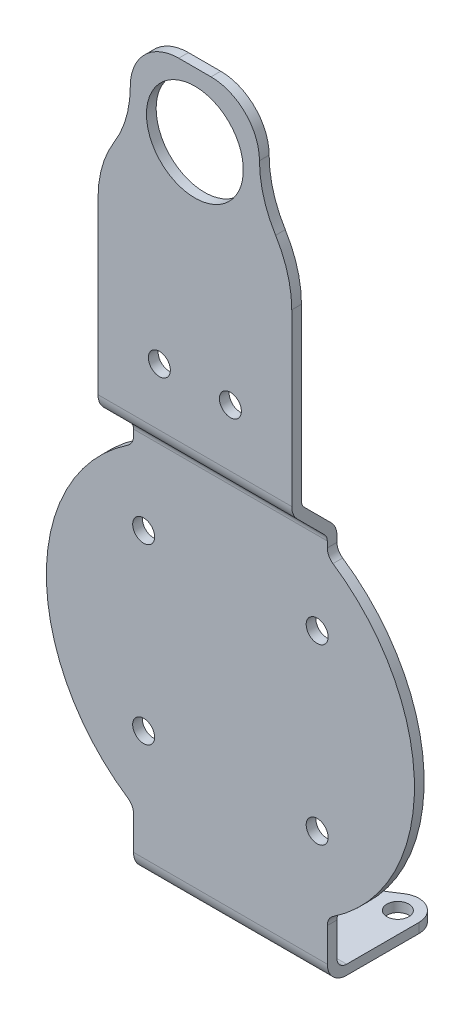
SolidWorks part; units mm, degrees
ref_plane "前视基准面" through (0, 0, 0) normal (0, 0, 1) x (1, 0, 0)
ref_plane "上视基准面" through (0, 0, 0) normal (0, 1, 0) x (1, 0, 0)
ref_plane "右视基准面" through (0, 0, 0) normal (1, 0, 0) x (0, 0, -1)
ref_plane "基准面1" through (15, 0, 0) normal (1, 0, 0) x (0, 0, -1)
sketch "草图1" plane through (15, 0, 0) normal (1, 0, 0) x (0, 0, -1)
  line L0 (-7, 32.3787) -> (-1.5, 26.8787)
  line L1 (-1.5, 26.8787) -> (-1.5, 32.3787)
  line L2 (-1.5, 32.3787) -> (-7, 32.3787)
extrude "凸台-拉伸1" add sketch "草图1" against normal blind 30
sketch "草图2" plane through (0, 0, 1.5) normal (0, 0, -1) x (-1, 0, 0)
  line L0 (-15, 24.2332) -> (-15, 32.3787)
  line L1 (-15, 32.3787) -> (15, 32.3787)
  line L2 (15, 32.3787) -> (15, 24.2332)
  line L3 (15, -24.2332) -> (-15, -24.2332)
  arc A0 (-15, -24.2332) -> (-15, 24.2332) centre (0, 0) cw
  arc A1 (15, 24.2332) -> (15, -24.2332) centre (0, 0) cw
extrude "凸台-拉伸2" add sketch "草图2" along normal blind 14.1773
sketch "草图3" plane through (0, -24.2332, 0) normal (0, -1, 0) x (1, 0, 0)
  line L0 (-15, -12.6773) -> (-15, 1.5)
  line L1 (-15, 1.5) -> (15, 1.5)
  line L2 (15, 1.5) -> (15, -12.6773)
  line L3 (15, -12.6773) -> (-15, -12.6773)
extrude "凸台-拉伸3" add sketch "草图3" along normal blind 7.7668
sketch "草图4" plane through (0, -32, 0) normal (0, -1, 0) x (1, 0, 0)
  line L0 (15, 1.5) -> (15, -12.6773)
  line L1 (-15, -12.6773) -> (-15, 1.5)
  line L2 (-15, 1.5) -> (15, 1.5)
  arc A0 (15, -12.6773) -> (9.8358, -15.3038) centre (11.75, -12.6773) cw
  arc A1 (9.8358, -15.3038) -> (-9.8358, -15.3038) centre (0, -28.8) ccw
  arc A2 (-9.8358, -15.3038) -> (-15, -12.6773) centre (-11.75, -12.6773) cw
extrude "凸台-拉伸4" add sketch "草图4" along normal blind 1.5
sketch "草图5" plane through (0, 0, -12.6773) normal (0, 0, -1) x (-1, 0, 0)
  line L0 (15, 24.2332) -> (15, 32.3787)
  line L1 (15, 32.3787) -> (-15, 32.3787)
  line L2 (-15, 32.3787) -> (-15, 24.2332)
  line L3 (-15, -24.2332) -> (-15, -32)
  line L4 (-15, -32) -> (0, -32)
  line L5 (0, -32) -> (15, -32)
  line L6 (15, -32) -> (15, -24.2332)
  arc A0 (-15, 24.2332) -> (-15, -24.2332) centre (0, 0) ccw
  arc A1 (15, -24.2332) -> (15, 24.2332) centre (0, 0) ccw
extrude "切除-拉伸1" cut sketch "草图5" against normal blind 0.5773
sketch "草图6" plane through (0, 0, -12.1) normal (0, 0, -1) x (-1, 0, 0)
  line L0 (15, 24.2332) -> (15, 32.3787)
  line L1 (15, 32.3787) -> (-15, 32.3787)
  line L2 (-15, 32.3787) -> (-15, 24.2332)
  line L3 (-15, -24.2332) -> (-15, -32)
  line L4 (-15, -32) -> (15, -32)
  line L5 (15, -32) -> (15, -24.2332)
  arc A0 (-15, 24.2332) -> (-15, -24.2332) centre (0, 0) ccw
  arc A1 (15, -24.2332) -> (15, 24.2332) centre (0, 0) ccw
extrude "切除-拉伸2" cut sketch "草图6" against normal blind 12.1
sketch "草图7" plane through (0, 32.3787, 0) normal (0, 1, 0) x (-1, 0, 0)
  line L0 (-15, 0) -> (-15, 7)
  line L1 (-15, 7) -> (15, 7)
  line L2 (15, 7) -> (15, 0)
  line L3 (15, 0) -> (-15, 0)
extrude "凸台-拉伸5" add sketch "草图7" along normal blind 52.6213
sketch "草图8" plane through (-15, 0, 0) normal (-1, 0, 0) x (0, 0, 1)
  line L0 (0, 27.5) -> (5.5, 33)
  line L1 (5.5, 33) -> (5.5, 85)
  line L2 (5.5, 85) -> (0, 85)
  line L3 (0, 85) -> (0, 27.5)
extrude "切除-拉伸3" cut sketch "草图8" against normal through all
sketch "草图9" plane through (0, 0, 7) normal (0, 0, 1) x (1, 0, 0)
  line L0 (-11.7954, 85) -> (-15, 85)
  line L1 (-15, 85) -> (-15, 60)
  arc A0 (-12.5, 68.75) -> (-11.7954, 85) centre (-26.5625, 77.5) ccw
  arc A1 (-15, 60) -> (-12.5, 68.75) centre (1.5625, 60) cw
extrude "切除-拉伸4" cut sketch "草图9" against normal through all
sketch "草图10" plane through (0, 0, 7) normal (0, 0, 1) x (1, 0, 0)
  line L0 (15, 60) -> (15, 85)
  line L1 (15, 85) -> (11.7954, 85)
  arc A0 (11.7954, 85) -> (12.5, 68.75) centre (26.5625, 77.5) ccw
  arc A1 (12.5, 68.75) -> (15, 60) centre (-1.5625, 60) cw
extrude "切除-拉伸5" cut sketch "草图10" against normal through all
hole_wizard "Ø3.4 (3.4) 直径孔1" positions "草图12" profile "草图11" hole size "Ø3.4" standard "ANSI Metric"
sketch "草图12" plane through (0, 0, 5.5) normal (0, 0, -1) x (-1, 0, 0)
  point P0 (5.5, 42.5)
  point P1 (-5.5, 42.5)
sketch "草图11" plane through (-5.5, 42.5, 5.5) normal (1, 0, 0) x (0, 1, 0)
  line L0 (0, 0) -> (0, 1.5)
  line L1 (0, 1.5) -> (1.7, 1.5)
  line L2 (1.7, 1.5) -> (1.7, 0)
  line L5 (1.7, 0) -> (0, 0)
  line L11 (0, -6.35) -> (0, 107.95) construction
  dimension "通孔孔直径" = 3.4
  dimension "通孔孔深度" = 1.5
hole_wizard "Ø3.4 (3.4) 直径孔2" positions "草图14" profile "草图13" hole size "Ø3.4" standard "ANSI Metric"
sketch "草图14" plane through (0, -32, 0) normal (0, 1, 0) x (1, 0, 0)
  point P0 (-11.75, 12.6773)
  point P1 (0, 8.85)
  point P2 (11.75, 12.6773)
sketch "草图13" plane through (-11.75, -32, -12.6773) normal (1, 0, 0) x (0, 0, 1)
  line L0 (0, 0) -> (0, 1.5)
  line L1 (0, 1.5) -> (1.7, 1.5)
  line L2 (1.7, 1.5) -> (1.7, 0)
  line L5 (1.7, 0) -> (0, 0)
  line L11 (0, -6.35) -> (0, 107.95) construction
  dimension "通孔孔直径" = 3.4
  dimension "通孔孔深度" = 1.5
hole_wizard "Ø15.0 (15) 直径孔1" positions "草图16" profile "草图15" hole size "Ø15.0" standard "ANSI Metric"
sketch "草图16" plane through (0, 0, 5.5) normal (0, 0, -1) x (-1, 0, 0)
  point P0 (0, 75)
sketch "草图15" plane through (0, 75, 5.5) normal (1, 0, 0) x (0, 1, 0)
  line L0 (0, 0) -> (0, 1.5)
  line L1 (0, 1.5) -> (7.5, 1.5)
  line L2 (7.5, 1.5) -> (7.5, 0)
  line L5 (7.5, 0) -> (0, 0)
  line L11 (0, -6.35) -> (0, 107.95) construction
  dimension "通孔孔直径" = 15
  dimension "通孔孔深度" = 1.5
hole_wizard "Ø3.4 (3.4) 直径孔3" positions "草图18" profile "草图17" hole size "Ø3.4" standard "ANSI Metric"
sketch "草图18" plane through (0, 0, 1.5) normal (0, 0, 1) x (1, 0, 0)
  point P0 (-13.435, -13.435)
  point P1 (-13.435, 13.435)
  point P2 (13.435, -13.435)
  point P3 (13.435, 13.435)
sketch "草图17" plane through (-13.435, -13.435, 1.5) normal (1, 0, 0) x (0, -1, 0)
  line L0 (0, 0) -> (0, 17.4273)
  line L1 (0, 17.4273) -> (1.7, 17.4273)
  line L2 (1.7, 17.4273) -> (1.7, 0)
  line L5 (1.7, 0) -> (0, 0)
  line L11 (0, -6.35) -> (0, 107.95) construction
  dimension "通孔孔直径" = 3.4
  dimension "通孔孔深度" = 17.4273
fillet "圆角1" radius 1.5 3 edges at (0, 26.8787, 1.5) (0, -32, 0) (0, 33, 5.5)
fillet "圆角2" radius 2 4 edges at (-15, -24.2332, 0.75) (-15, 24.2332, 0.75) (15, 24.2332, 0.75) (15, -24.2332, 0.75)
fillet "圆角3" radius 3 3 edges at (0, 32.3787, 7) (0, 27.5, 0) (0, -33.5, 1.5)
fillet "圆角4" radius 7.5 2 edges at (11.7954, 85, 6.25) (-11.7954, 85, 6.25)
